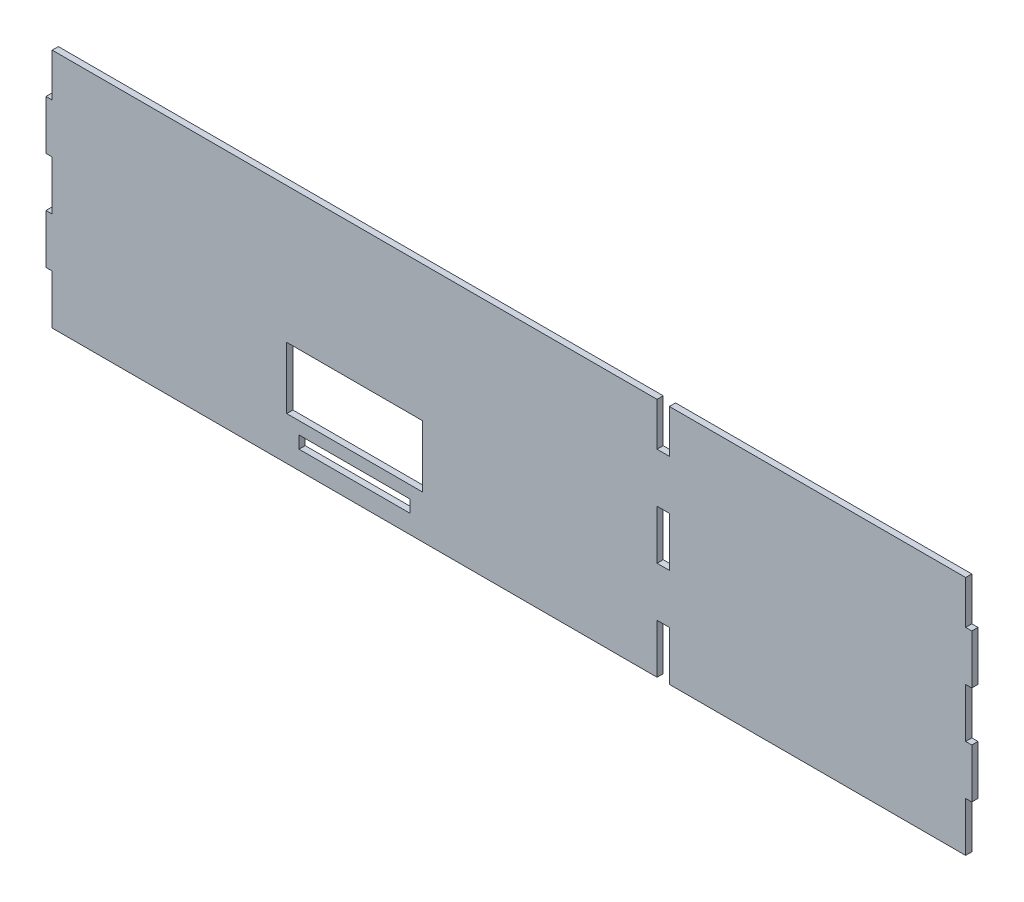
SolidWorks part; units mm, degrees
material "Contreplaqué pin"
ref_plane "Plan de face" through (0, 0, 0) normal (0, 0, 1) x (1, 0, 0)
ref_plane "Plan de dessus" through (0, 0, 0) normal (0, 1, 0) x (1, 0, 0)
ref_plane "Plan de droite" through (0, 0, 0) normal (1, 0, 0) x (0, 0, -1)
sketch "Esquisse1" plane through (0, 0, 0) normal (0, 0, 1) x (1, 0, 0)
  line L0 (750, 120) -> (750, 160)
  line L1 (5, 0) -> (745, 0)
  line L2 (0, 40) -> (0, 80)
  line L4 (750, 40) -> (750, 80)
  line L7 (745, 160) -> (750, 160)
  line L11 (750, 40) -> (745, 40)
  line L12 (745, 0) -> (745, 40)
  line L13 (750, 80) -> (745, 80)
  line L15 (750, 120) -> (745, 120)
  line L16 (745, 80) -> (745, 120)
  line L17 (0, 120) -> (0, 160)
  line L18 (0, 160) -> (5, 160)
  line L21 (5, 160) -> (5, 195)
  line L22 (0, 120) -> (5, 120)
  line L24 (0, 80) -> (5, 80)
  line L25 (5, 120) -> (5, 80)
  line L26 (0, 40) -> (5, 40)
  line L29 (5, 40) -> (5, 0)
  line L81 (500, 195) -> (500, 0) construction
  line L96 (745, 195) -> (5, 195)
  line L97 (745, 195) -> (745, 160)
  line L98 (745, 120) -> (745, 80)
  line L100 (195, 85) -> (305, 85)
  line L101 (195, 85) -> (195, 35)
  line L102 (195, 35) -> (305, 35)
  line L103 (305, 85) -> (305, 35)
  line L104 (505, 160) -> (495, 160)
  line L105 (505, 160) -> (505, 195)
  line L106 (505, 195) -> (495, 195)
  line L107 (495, 160) -> (495, 195)
  line L108 (505, 120) -> (495, 120)
  line L109 (505, 120) -> (505, 80)
  line L110 (505, 80) -> (495, 80)
  line L111 (495, 120) -> (495, 80)
  line L112 (505, 40) -> (495, 40)
  line L113 (505, 40) -> (505, 0)
  line L114 (505, 0) -> (495, 0)
  line L115 (495, 40) -> (495, 0)
  point P57 (250, 35)
  point P58 (195, 60)
  dimension "D1" = 5
  dimension "D2" = 750
  dimension "D3" = 5
  dimension "D4" = 195
  dimension "D5" = 40
  dimension "D6" = 35
  dimension "D7" = 40
  dimension "D8" = 35
  dimension "D9" = 10
  dimension "D11" = 500
  dimension "D18" = 50
  dimension "D19" = 110
  dimension "D20" = 250
  dimension "D21" = 60
extrude "Boss.-Extru.1" add sketch "Esquisse1" along normal blind 5
sketch "Esquisse2" plane through (0, 0, 5) normal (0, 0, 1) x (1, 0, 0)
  line L0 (195, 35) -> (305, 35) construction
  line L1 (205, 25) -> (295, 25)
  line L2 (205, 25) -> (205, 15)
  line L3 (205, 15) -> (295, 15)
  line L4 (295, 25) -> (295, 15)
  point P4 (250, 25)
  point P7 (250, 35)
  dimension "D1" = 10
  dimension "D2" = 10
  dimension "D3" = 90
extrude "Enlèv. mat.-Extru.1" cut sketch "Esquisse2" against normal up to next
